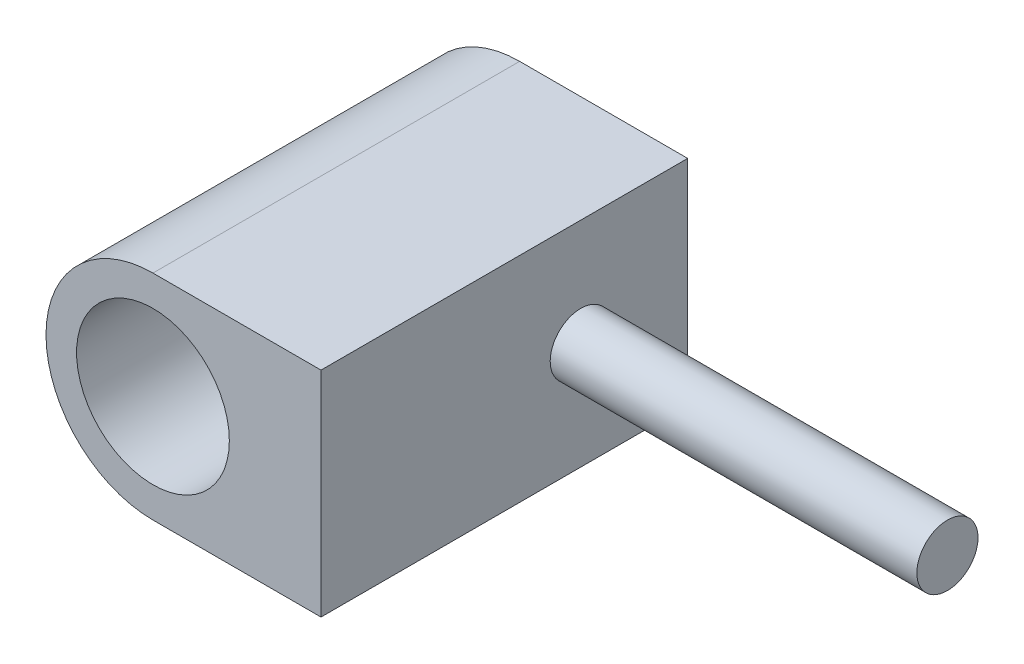
SolidWorks part; units mm, degrees
material "Teak"
ref_plane "Front Plane" through (0, 0, 0) normal (0, 0, 1) x (1, 0, 0)
ref_plane "Top Plane" through (0, 0, 0) normal (0, 1, 0) x (1, 0, 0)
ref_plane "Right Plane" through (0, 0, 0) normal (1, 0, 0) x (0, 0, -1)
sketch "Sketch1" plane through (0, 0, 0) normal (0, 0, 1) x (1, 0, 0)
  line L1 (0, 0) -> (-55, 0)
  line L2 (0, 0) -> (0, 70)
  line L3 (0, 70) -> (-55, 70)
  arc A0 (-55, 70) -> (-55, 0) centre (-55, 35) ccw
  circle A1 centre (-55, 35) radius 20
  dimension "D5" = 70
  dimension "D6" = 40
  dimension "D1" = 70
  dimension "D4" = 35
extrude "Boss-Extrude1" add sketch "Sketch1" along normal blind 120
sketch "Sketch2" plane through (0, 0, 120) normal (0, 0, 1) x (1, 0, 0)
  circle A0 centre (-55, 35) radius 25
  dimension "D1" = 50
extrude "Cut-Extrude1" cut sketch "Sketch2" against normal blind 110
sketch "Sketch3" plane through (0, 0, 0) normal (1, 0, 0) x (0, 0, -1)
  line L0 (0, 0) -> (0, 70) construction
  line L1 (-120, 70) -> (0, 70) construction
  circle A0 centre (-35, 35) radius 10
  dimension "D1" = 20
  dimension "D3" = 35
  dimension "D2" = 35
extrude "Boss-Extrude2" add sketch "Sketch3" along normal blind 120
